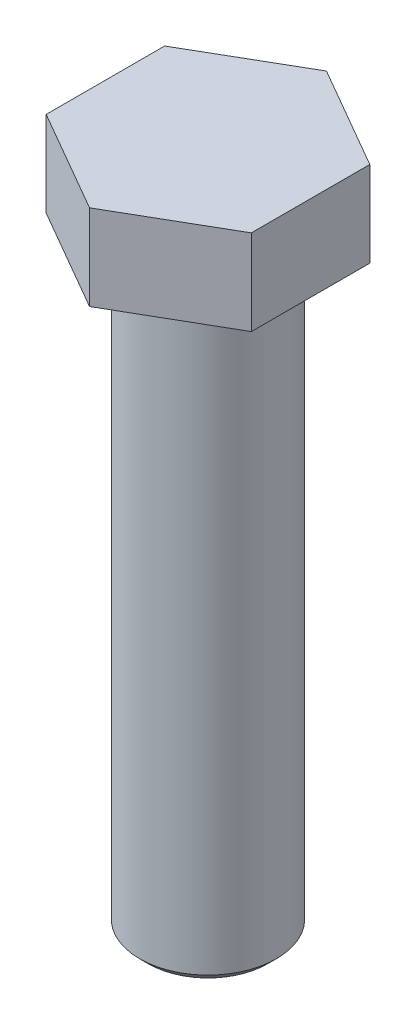
SolidWorks part; units mm, degrees
ref_plane "Front Plane" through (0, 0, 0) normal (0, 0, 1) x (1, 0, 0)
ref_plane "Top Plane" through (0, 0, 0) normal (0, 1, 0) x (1, 0, 0)
ref_plane "Right Plane" through (0, 0, 0) normal (1, 0, 0) x (0, 0, -1)
sketch "Sketch1" plane through (0, 0, 0) normal (0, 1, 0) x (1, 0, 0)
  circle A0 centre (0, 0) radius 4
  dimension "D1" = 8
extrude "Boss-Extrude1" add sketch "Sketch1" along normal blind 35
sketch "Sketch2" plane through (0, 35, 0) normal (0, 1, 0) x (1, 0, 0)
  line L1 (6, 3.4641) -> (0, 6.9282)
  line L2 (0, 6.9282) -> (-6, 3.4641)
  line L3 (-6, 3.4641) -> (-6, -3.4641)
  line L4 (-6, -3.4641) -> (0, -6.9282)
  line L5 (0, -6.9282) -> (6, -3.4641)
  line L6 (6, -3.4641) -> (6, 3.4641)
  circle A0 centre (0, 0) radius 6 construction
  dimension "D1" = 12
extrude "Boss-Extrude2" add sketch "Sketch2" along normal blind 5
chamfer "Chamfer1" distance 0.5 angle 45 1 edges at (0, 0, 4)
